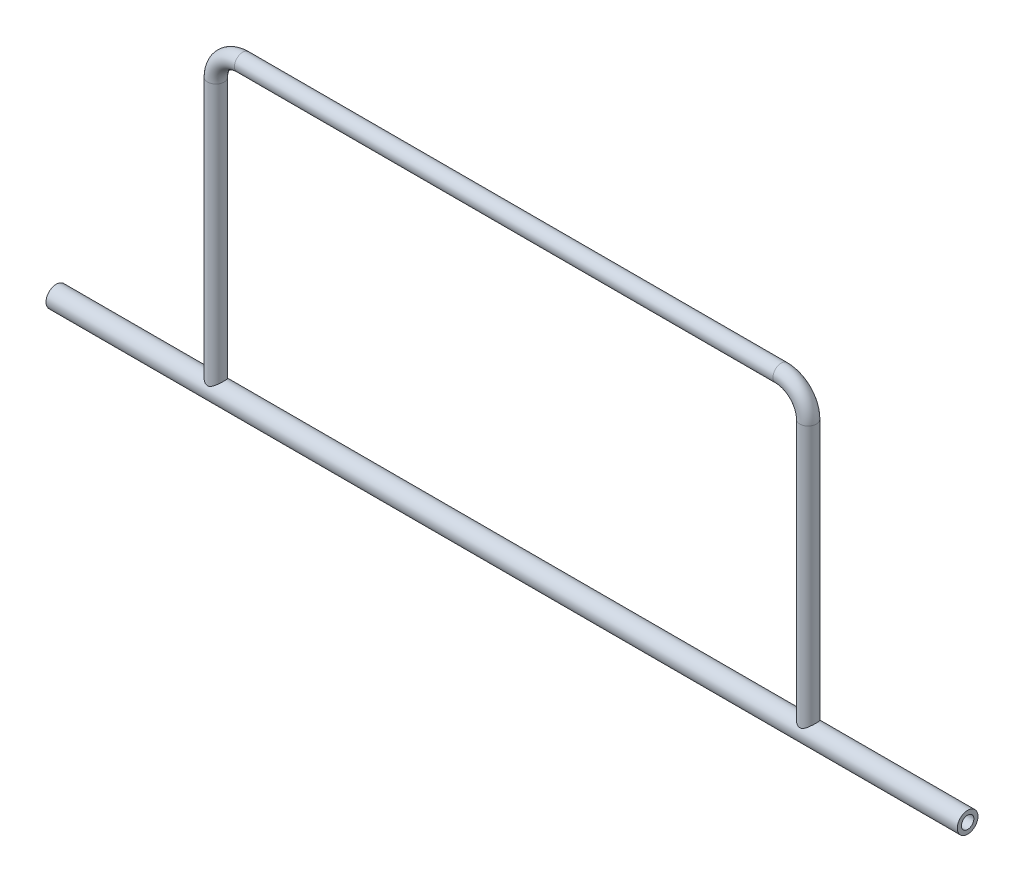
SolidWorks part; units mm, degrees
ref_plane "Front Plane" through (0, 0, 0) normal (0, 0, 1) x (1, 0, 0)
ref_plane "Top Plane" through (0, 0, 0) normal (0, 1, 0) x (1, 0, 0)
ref_plane "Right Plane" through (0, 0, 0) normal (1, 0, 0) x (0, 0, -1)
sketch "Sketch1" plane through (0, 0, 0) normal (1, 0, 0) x (0, 0, -1)
  circle A0 centre (0, 0) radius 5
  dimension "D1" = 10
extrude "Boss-Extrude1" add sketch "Sketch1" against normal blind 220
sketch "Sketch2" plane through (0, 0, 0) normal (0, 0, 1) x (1, 0, 0)
  line L0 (-220, 0) -> (0, 0) construction
  line L1 (-220, 5) -> (-220, -5) construction
  line L2 (-143, 0) -> (-143, 130)
  line L3 (-130, 143) -> (0, 143)
  line L4 (0, 143) -> (0, 0) construction
  arc A0 (-143, 130) -> (-130, 143) centre (-130, 130) cw
  dimension "D1" = 77
  dimension "D2" = 130
  dimension "D3" = 130
sweep "Sweep1" add path "Sketch2" circular profile diameter 8 parameters "D3"=8
sketch "Sketch9" plane through (0, 0, 0) normal (1, 0, 0) x (0, 0, -1)
  circle A0 centre (0, 0) radius 3
  dimension "D1" = 6
extrude "Cut-Extrude1" cut sketch "Sketch9" against normal up to surface (220 mm away) up to face at (-220, 0, -5)
mirror "Mirror1" about plane through (0, 0, 0) normal (1, 0, 0) of "Cut-Extrude1", "Sweep1", "Boss-Extrude1"
